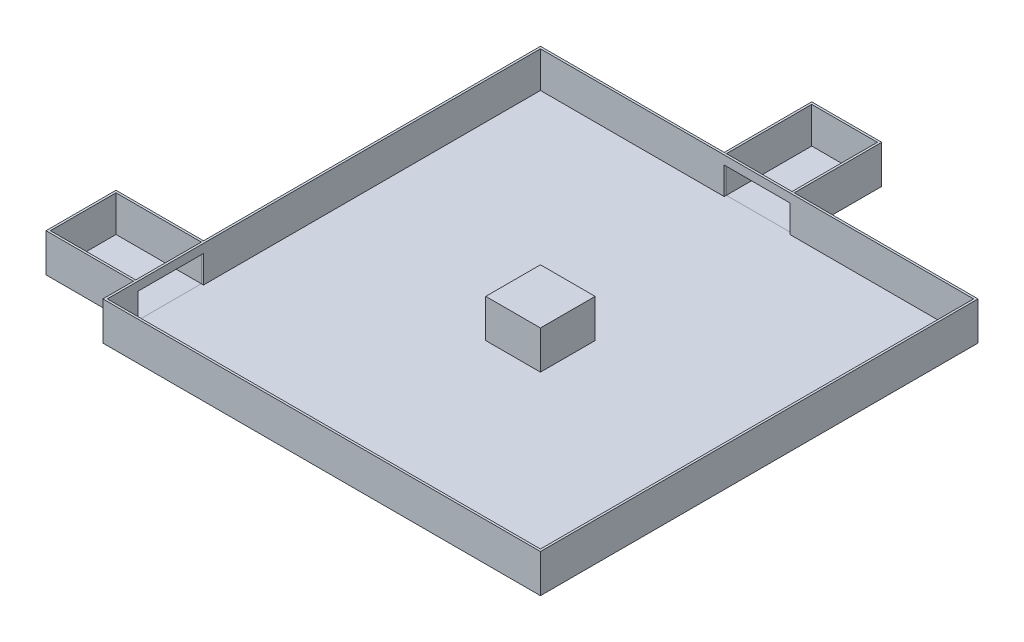
SolidWorks part; units mm, degrees
ref_plane "前视基准面" through (0, 0, 0) normal (0, 0, 1) x (1, 0, 0)
ref_plane "上视基准面" through (0, 0, 0) normal (0, 1, 0) x (1, 0, 0)
ref_plane "右视基准面" through (0, 0, 0) normal (1, 0, 0) x (0, 0, -1)
other "Configuration Table"
sketch "草图1" plane through (0, 0, 0) normal (0, 1, 0) x (1, 0, 0)
  line L0 (0, 0) -> (0, 4000)
  line L1 (0, 4000) -> (4000, 4000)
  line L2 (4000, 4000) -> (4000, 0)
  line L3 (4000, 0) -> (0, 0)
  dimension "D1" = 4000
  dimension "D2" = 4000
  dimension "D3" = 4000
extrude "凸台-拉伸1" add sketch "草图1" along normal blind 350 contours L3 L0 L1 L2
sketch "草图2" plane through (0, 350, 0) normal (0, 1, 0) x (1, 0, 0)
  line L0 (20, 3980) -> (3980, 3980)
  line L1 (3980, 3980) -> (3980, 20)
  line L2 (3980, 20) -> (20, 20)
  line L3 (20, 20) -> (20, 3980)
  line L4 (4000, 4000) -> (4000, 0) construction
  line L5 (0, 4000) -> (4000, 4000) construction
  line L6 (0, 0) -> (0, 4000) construction
  line L7 (4000, 0) -> (0, 0) construction
  dimension "D1" = 20
  dimension "D2" = 20
  dimension "D3" = 20
  dimension "D4" = 20
extrude "切除-拉伸1" cut sketch "草图2" against normal blind 330
sketch "草图3" plane through (0, 0, -4000) normal (0, 0, -1) x (-1, 0, 0)
  line L0 (-2000, 643.7534) -> (-2000, -168.5082) construction
  line L1 (-1700, 270) -> (-2300, 270)
  line L2 (-2300, 270) -> (-2300, 20)
  line L3 (-2300, 20) -> (-1700, 20)
  line L4 (-1700, 270) -> (-1700, 20)
  line L5 (0, 0) -> (-4000, 0) construction
  line L6 (0, 350) -> (0, 0) construction
  point P7 (-2000, 20)
  point P8 (-2000, 270)
  dimension "D1" = 600
  dimension "D2" = 250
  dimension "D3" = 20
  dimension "D4" = 1700
extrude "切除-拉伸2" cut sketch "草图3" against normal blind 20
sketch "草图5" plane through (0, 0, 0) normal (-1, 0, 0) x (0, 0, 1)
  line L0 (-600, 365.7553) -> (-600, -137.7591) construction
  line L1 (-300, 20) -> (-900, 20)
  line L2 (-900, 20) -> (-900, 270)
  line L3 (-900, 270) -> (-300, 270)
  line L4 (-300, 20) -> (-300, 270)
  line L5 (0, 0) -> (-4000, 0) construction
  line L6 (0, 350) -> (0, 0) construction
  point P2 (-600, 270)
  point P8 (-600, 20)
  dimension "D1" = 20
  dimension "D2" = 250
  dimension "D3" = 600
  dimension "D4" = 300
extrude "切除-拉伸3" cut sketch "草图5" against normal blind 20
sketch "草图6" plane through (0, 20, 0) normal (0, 1, 0) x (1, 0, 0)
  line L0 (4417.4375, 2000) -> (-502.2256, 2000) construction
  line L1 (2000, 4803.7985) -> (2000, -159.9476) construction
  line L2 (2250, 2250) -> (2250, 1750)
  line L3 (2250, 1750) -> (1750, 1750)
  line L4 (1750, 2250) -> (1750, 1750)
  line L5 (2250, 2250) -> (1750, 2250)
  line L6 (20, 20) -> (3980, 20) construction
  line L7 (3980, 3980) -> (20, 3980) construction
  line L8 (20, 3980) -> (20, 900) construction
  line L9 (3980, 20) -> (3980, 3980) construction
  point P9 (2000, 1750)
  point P10 (1750, 2000)
  point P11 (2250, 2000)
  dimension "D1" = 1730
  dimension "D2" = 1730
  dimension "D3" = 1730
  dimension "D4" = 1730
extrude "凸台-拉伸2" add sketch "草图6" along normal blind 350
sketch "草图19" plane through (0, 0, 0) normal (0, -1, 0) x (1, 0, 0)
  line L0 (2000, -4648.259) -> (2000, 376.8578) construction
  line L1 (-800, -600) -> (4641.0633, -600) construction
  line L2 (4000, 0) -> (0, 0) construction
  line L3 (2320, -4000) -> (2320, -4800)
  line L4 (0, -4000) -> (4000, -4000) construction
  line L5 (2320, -4800) -> (1680, -4800)
  line L6 (1680, -4800) -> (1680, -4000)
  line L7 (1680, -4000) -> (2320, -4000)
  line L8 (0, 0) -> (0, -4000) construction
  line L9 (4000, -4000) -> (4000, 0) construction
  line L10 (0, -920) -> (-800, -920)
  line L11 (-800, -920) -> (-800, -280)
  line L12 (-800, -280) -> (0, -280)
  line L13 (0, -280) -> (0, -920)
  dimension "D1" = 600
  dimension "D2" = 1680
  dimension "D3" = 1680
  dimension "D4" = 800
  dimension "D5" = 280
  dimension "D6" = 640
  dimension "D7" = 800
extrude "凸台-拉伸10" add sketch "草图19" against normal blind 350 separate body
sketch "草图20" plane through (0, 350, 0) normal (0, 1, 0) x (1, 0, 0)
  line L0 (2300, 4000) -> (1700, 4000)
  line L1 (1700, 4000) -> (1700, 4780)
  line L2 (1700, 4780) -> (2300, 4780)
  line L3 (2300, 4780) -> (2300, 4000)
  line L4 (3980, 3980) -> (20, 3980) construction
  line L5 (1680, 4000) -> (1680, 4800) construction
  line L6 (2320, 4800) -> (2320, 4000) construction
  line L7 (1680, 4800) -> (2320, 4800) construction
  line L8 (0, 900) -> (0, 300)
  line L9 (0, 300) -> (-780, 300)
  line L10 (-780, 300) -> (-780, 900)
  line L11 (-780, 900) -> (0, 900)
  line L12 (20, 3980) -> (20, 20) construction
  line L13 (-800, 920) -> (0, 920) construction
  line L14 (0, 280) -> (-800, 280) construction
  line L15 (-800, 280) -> (-800, 920) construction
  dimension "D1" = 20
  dimension "D2" = 20
  dimension "D3" = 20
  dimension "D4" = 20
  dimension "D5" = 20
  dimension "D6" = 20
  dimension "D7" = 20
  dimension "D8" = 20
extrude "切除-拉伸7" cut sketch "草图20" against normal blind 330
